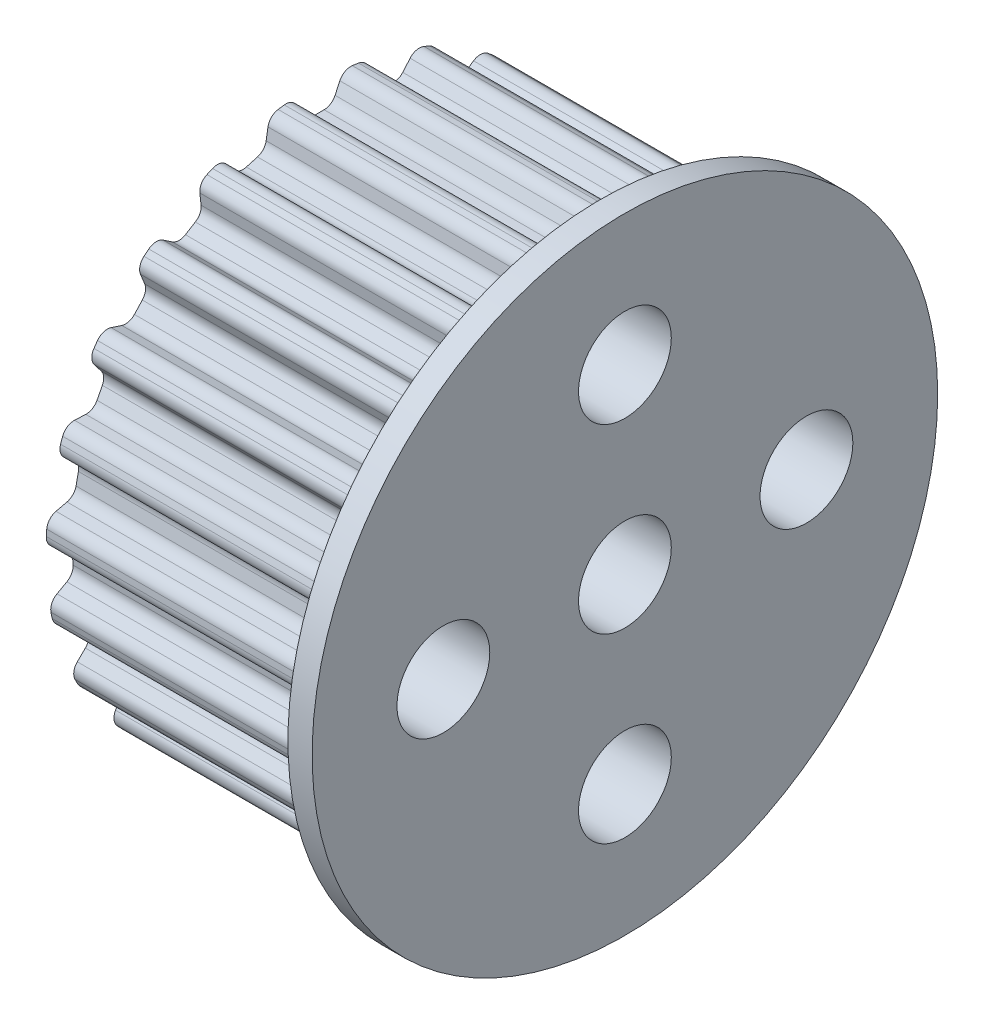
SolidWorks part; units mm, degrees
ref_plane "Front Plane" through (0, 0, 0) normal (0, 0, 1) x (1, 0, 0)
ref_plane "Top Plane" through (0, 0, 0) normal (0, 1, 0) x (1, 0, 0)
ref_plane "Right Plane" through (0, 0, 0) normal (1, 0, 0) x (0, 0, -1)
sketch "Sketch1" plane through (0, 0, 0) normal (1, 0, 0) x (0, 0, -1)
  line L0 (-0.5338, 6.5292) -> (-0.4158, 6.2761)
  line L1 (-0.1439, 6.1029) -> (0.1439, 6.1029)
  line L2 (0.4158, 6.2761) -> (0.5338, 6.5292)
  line L3 (-0.9195, 6.69) -> (0, 0)
  line L4 (0, 0) -> (0.9195, 6.69)
  arc A0 (-0.9195, 6.69) -> (-0.8431, 6.7001) centre (0, 0) cw
  arc A1 (0.8431, 6.7001) -> (0.9195, 6.69) centre (0, 0) cw
  arc A2 (-0.6246, 6.724) -> (0.6246, 6.724) centre (0, 0) cw construction
  arc A3 (0.5338, 6.5292) -> (0.8431, 6.7001) centre (0.8057, 6.4024) cw
  arc A4 (0.1439, 6.1029) -> (0.4158, 6.2761) centre (0.1439, 6.4029) ccw
  arc A5 (-0.4158, 6.2761) -> (-0.1439, 6.1029) centre (-0.1439, 6.4029) ccw
  arc A6 (-0.8431, 6.7001) -> (-0.5338, 6.5292) centre (-0.8057, 6.4024) cw
  arc A7 (-1.0148, 7.3835) -> (1.0148, 7.3835) centre (0, 0) cw construction
  point P1 (0, 6.7529)
  point P3 (0, 6.1029)
  point P21 (0.335, 6.1029)
  point P24 (-0.335, 6.1029)
  dimension "D6" = 0.3
  dimension "D1" = 115
  dimension "D2" = 115
  dimension "D3" = 0.67
  dimension "D5" = 0.65
  dimension "D4" = 15.652
  dimension "D8" = 0.7
  dimension "D7" = 2.036
extrude "Boss-Extrude1" add sketch "Sketch1" along normal blind 7
pattern_circular "CirPattern1" count 23 over 360 about axis through (0, 0, 0) along (1, 0, 0) of "Boss-Extrude1"
sketch "Sketch2" plane through (7, 0, 0) normal (1, 0, 0) x (0, 0, -1)
  circle A0 centre (0, 0) radius 1.15
  circle A1 centre (0, 4.5) radius 1.15
  circle A2 centre (4.5, 0) radius 1.15
  circle A3 centre (0, -4.5) radius 1.15
  circle A4 centre (-4.5, 0) radius 1.15
  point P14 (0, 0)
  dimension "D1" = 2.3
  dimension "D2" = 4.5
  dimension "D3" = 4
extrude "Cut-Extrude1" cut sketch "Sketch2" against normal through all
sketch "Sketch3" plane through (7, 0, 0) normal (1, 0, 0) x (0, 0, -1)
  circle A0 centre (0, 0) radius 7.7529
  circle A1 centre (0, 0) radius 1.15
  arc A2 (-6.3368, 2.3339) -> (-6.3884, 2.1887) centre (0, 0) ccw construction
  circle A3 centre (-4.5, 0) radius 1.15
  circle A4 centre (0, -4.5) radius 1.15 construction
  circle A5 centre (4.5, 0) radius 1.15 construction
  circle A6 centre (0, 4.5) radius 1.15 construction
  circle A7 centre (0, -4.5) radius 1.15
  circle A8 centre (4.5, 0) radius 1.15
  circle A9 centre (0, 4.5) radius 1.15
  dimension "D1" = 1
extrude "Boss-Extrude2" add sketch "Sketch3" along normal blind 0.6
equation "\"teeth\"= 23"
equation "\"angle\"= 360 / \"teeth\""
equation "\"D4@Sketch1\"=\"angle\""
equation "\"D1@CirPattern1\"=\"teeth\""
